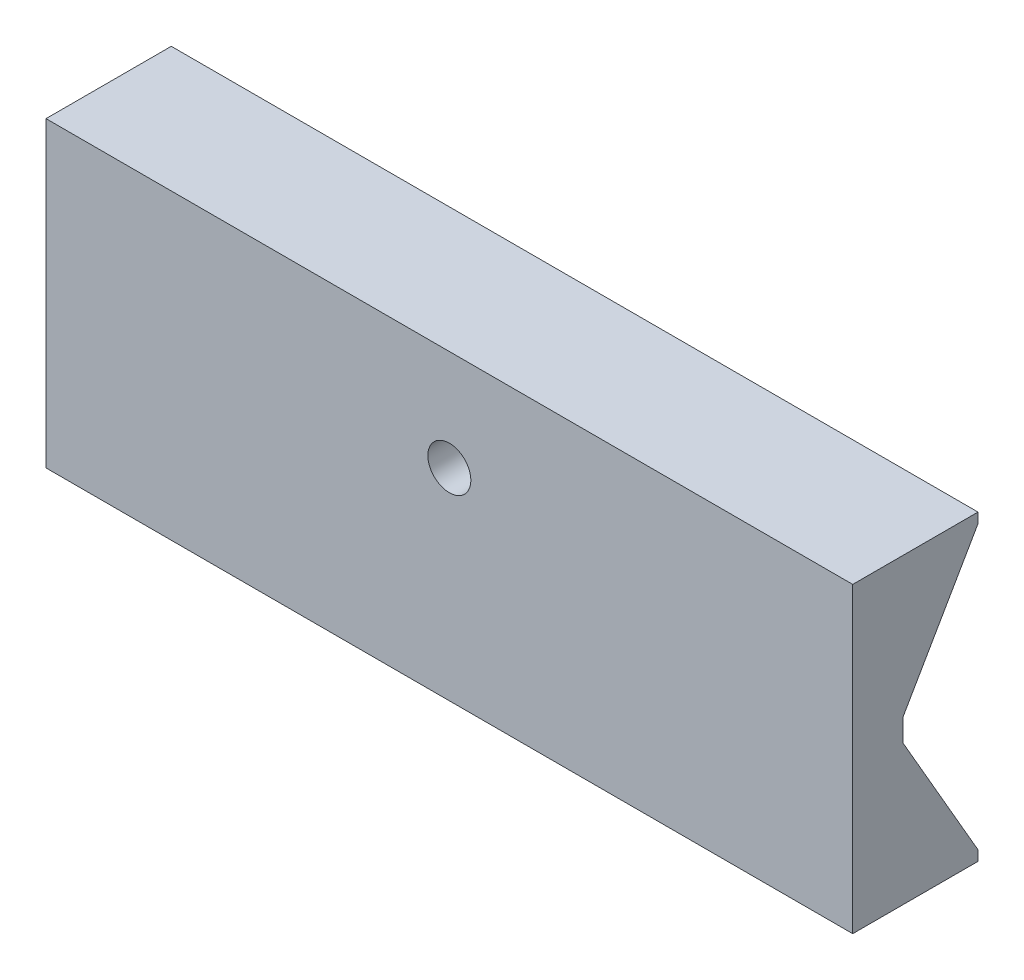
SolidWorks part; units mm, degrees
material "6061 Alloy"
ref_plane "Front Plane" through (0, 0, 0) normal (0, 0, 1) x (1, 0, 0)
ref_plane "Top Plane" through (0, 0, 0) normal (0, 1, 0) x (1, 0, 0)
ref_plane "Right Plane" through (0, 0, 0) normal (1, 0, 0) x (0, 0, -1)
sketch "Sketch1" plane through (0, 0, 0) normal (1, 0, 0) x (0, 0, -1)
  line L0 (0, -19.05) -> (16.51, -19.05) construction
  line L1 (16.51, -19.05) -> (6.35, -1.4524) construction
  line L2 (6.35, 1.4524) -> (16.51, 19.05) construction
  line L3 (16.51, 19.05) -> (0, 19.05) construction
  line L4 (0, 19.05) -> (0, -19.05)
  line L5 (6.35, 1.4524) -> (15.7768, 17.78)
  line L6 (0, 0) -> (6.35, 0) construction
  line L7 (6.35, 1.4524) -> (6.35, -1.4524)
  line L8 (15.7768, 17.78) -> (15.7768, 19.05)
  line L9 (6.35, -1.4524) -> (15.7768, -17.78)
  line L10 (15.7768, -17.78) -> (15.7768, -19.05)
  line L11 (15.7768, 19.05) -> (0, 19.05)
  line L12 (0, -19.05) -> (15.7768, -19.05)
  circle A0 centre (20.1762, 0) radius 12.7 construction
  dimension "D5" = 25.4
  dimension "D1" = 38.1
  dimension "D2" = 120
  dimension "D3" = 6.35
  dimension "D4" = 10.16
  dimension "D6" = 1.27
extrude "Boss-Extrude1" add sketch "Sketch1" along normal blind 101.6
hole_wizard "1/4-28 Tapped Hole1" positions "Sketch3" profile "Sketch2" tap size "1/4-28" standard "ANSI Inch" end condition through all
sketch "Sketch3" plane through (0, 0, 0) normal (0, 0, 1) x (1, 0, 0)
  line L0 (50.8, 19.05) -> (50.8, -19.05) construction
  line L3 (101.6, 19.05) -> (0, 19.05) construction
  line L4 (101.6, 0) -> (0, 0) construction
  line L5 (101.6, 19.05) -> (101.6, -19.05) construction
  line L6 (0, 19.05) -> (0, -19.05) construction
  point P0 (50.8, 6.35)
  dimension "D1" = 6.35
sketch "Sketch2" plane through (50.8, 6.35, 0) normal (1, 0, 0) x (0, -1, 0)
  line L0 (0, 0) -> (0, 15.7768)
  line L1 (0, 15.7768) -> (2.7051, 15.7768)
  line L2 (2.7051, 15.7768) -> (2.7051, 0)
  line L5 (2.7051, 0) -> (0, 0)
  line L11 (0, -6.35) -> (0, 107.95) construction
  dimension "Thru Tap Drill Dia." = 5.4102
  dimension "Thru Tap Drill Depth" = 15.7768
cosmetic thread "Hole Thread1" parameters "D1"=9.1818, "D2"=6.35
equation "\"delta-z\"= 1.5"
equation "\"max-tube-diam\"= 3.5"
equation "\"v-block-notch-height\"= 1.5"
equation "\"v-block-notch-angle\"= 120"
equation "\"jaw-travel\"= 4.45"
equation "\"D1@Sketch1\"=\"v-block-notch-height\""
equation "\"D2@Sketch1\"=\"v-block-notch-angle\""
equation "\"total-height\"= 3.28"
equation "\"mid-height\"= 1.5"
equation "\"jaw-width\"= 4"
equation "\"jaw-height\"= \"total-height\" - \"mid-height\""
equation "\"jaw-mod-plate-thickness\"= .375"
equation "\"jaw-mod-height\"=  \"max-tube-diam\"/2 + \"delta-z\" + \"v-block-notch-height\"/2"
equation "\"rib-top-width\"= 0.5"
equation "\"rib-side-width\"= 0.5"
equation "\"quarter-twenty-close-clearance\"= .257"
equation "\"box-way-width\"= 1.5"
equation "\"box-way-depth\"= 1.5"
equation "\"screw-OD\"= .625"
equation "\"screw-reduced-diam\"= .47"
equation "\"pressure-plate-OD\"= 6.75"
equation "\"swivel-cleat-thick\"= .5"
equation "\"swivel-gap\"= .02"
equation "\"D1@Boss-Extrude1\"=\"jaw-width\""
